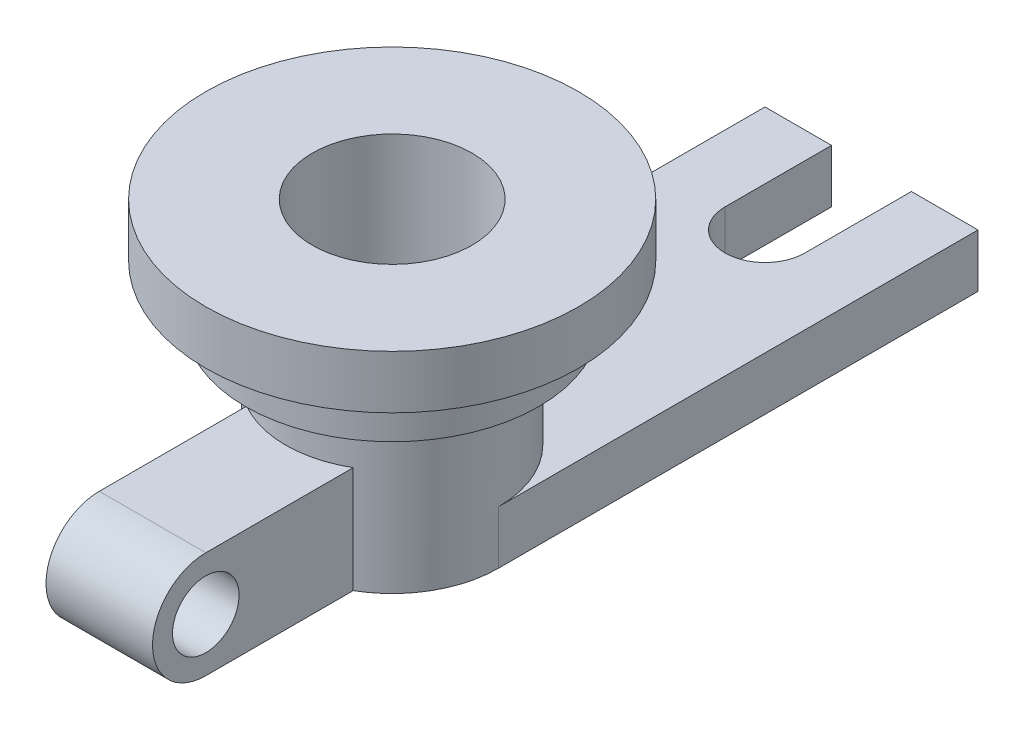
SolidWorks part; units mm, degrees
ref_plane "Front Plane" through (0, 0, 0) normal (0, 0, 1) x (1, 0, 0)
ref_plane "Top Plane" through (0, 0, 0) normal (0, 1, 0) x (1, 0, 0)
ref_plane "Right Plane" through (0, 0, 0) normal (1, 0, 0) x (0, 0, -1)
sketch "Sketch2" plane through (0, 0, 0) normal (0, 0, 1) x (1, 0, 0)
  line L0 (0, 0) -> (0, 114.9457) construction
  line L1 (-30, 0) -> (-30, 100)
  line L2 (-30, 100) -> (-70, 100)
  line L3 (-70, 100) -> (-70, 80)
  line L4 (-70, 80) -> (-55, 80)
  line L5 (-55, 80) -> (-55, 60)
  line L6 (-55, 60) -> (-40, 60)
  line L7 (-40, 60) -> (-40, 0)
  line L8 (-40, 0) -> (-30, 0)
  point P10 (-42.7172, 76.7534)
  point P12 (-42.761, 60)
  point P13 (-43.1279, 60)
  dimension "D1" = 60
  dimension "D2" = 40
  dimension "D3" = 20
  dimension "D4" = 140
  dimension "D5" = 110
  dimension "D6" = 100
  dimension "D7" = 80
revolve "Revolve1" add sketch "Sketch2" angle 360 about L0
sketch "Sketch4" plane through (0, 0, 0) normal (0, 1, 0) x (1, 0, 0)
  line L0 (-15, 140) -> (-15, 180)
  line L1 (-15, 180) -> (-40, 180)
  line L2 (-40, 180) -> (-40, 0)
  line L3 (0, 0) -> (0, 211.7574) construction
  line L4 (40, 180) -> (40, 0)
  line L5 (15, 180) -> (40, 180)
  line L6 (15, 140) -> (15, 180)
  arc A0 (-15, 140) -> (15, 140) centre (0, 140) ccw
  circle A1 centre (0, 0) radius 70 construction
  circle A3 centre (0, 0) radius 40 construction
  arc A4 (40, 0) -> (-40, 0) centre (0, 0) ccw
  point P1 (0, 0)
  point P12 (40, 180)
  point P17 (10.1741, 38.6845)
  dimension "D1" = 30
  dimension "D2" = 180
  dimension "D3" = 80
  dimension "D4" = 40
extrude "Boss-Extrude1" add sketch "Sketch4" along normal blind 20
sketch "Sketch3" plane through (0, 0, 0) normal (-1, 0, 0) x (0, 0, 1)
  line L0 (30, 0) -> (30, 40)
  line L2 (30, 40) -> (90, 40)
  line L4 (90, 0) -> (30, 0)
  line L5 (-180, 20) -> (-180, 0) construction
  circle A1 centre (90, 20) radius 12.5
  arc A2 (90, 0) -> (90, 40) centre (90, 20) ccw
  point P2 (0, 0)
  point P10 (36.5827, 40)
  point P11 (32.0345, 40)
  point P12 (0, 0)
  point P13 (0, 0)
  point P14 (0, 0)
  point P15 (0, 0)
  dimension "D1" = 20
  dimension "D2" = 25
  dimension "D3" = 270
  dimension "D4" = 40
extrude "Boss-Extrude2" add sketch "Sketch3" along normal mid plane 40
